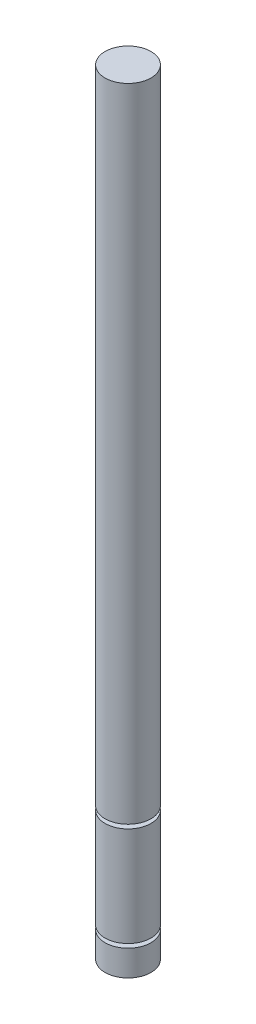
SolidWorks part; units mm, degrees
ref_plane "Front Plane" through (0, 0, 0) normal (0, 0, 1) x (1, 0, 0)
ref_plane "Top Plane" through (0, 0, 0) normal (0, 1, 0) x (1, 0, 0)
ref_plane "Right Plane" through (0, 0, 0) normal (1, 0, 0) x (0, 0, -1)
sketch "Sketch1" plane through (0, 0, 0) normal (0, 1, 0) x (1, 0, 0)
  circle A0 centre (0, 0) radius 4
  dimension "D1" = 8
extrude "Boss-Extrude1" add sketch "Sketch1" along normal blind 135
sketch "Sketch2" plane through (0, 0, 0) normal (0, 0, 1) x (1, 0, 0)
  line L0 (0, 0) -> (0, 50000) construction
  line L1 (-4, 135) -> (-4, 0) construction
  line L2 (-4, 5.2) -> (-3, 5.2)
  line L3 (-4, 5.2) -> (-4, 4.5)
  line L4 (-4, 4.5) -> (-3, 4.5)
  line L5 (-3, 5.2) -> (-3, 4.5)
  line L6 (-4, 0) -> (4, 0) construction
  point P9 (-3.5, 5.2)
  dimension "D1" = 1
  dimension "D2" = 0.7
  dimension "D3" = 5.2
revolve "Cut-Revolve1" cut sketch "Sketch2" angle 360 about L0
sketch "Sketch3" plane through (0, 0, 0) normal (0, 0, 1) x (1, 0, 0)
  line L0 (0, 2.24) -> (0, 20.2009) construction
pattern_linear "LPattern1" count 2 spacing 18 along (0, 1, 0) of "Cut-Revolve1"
